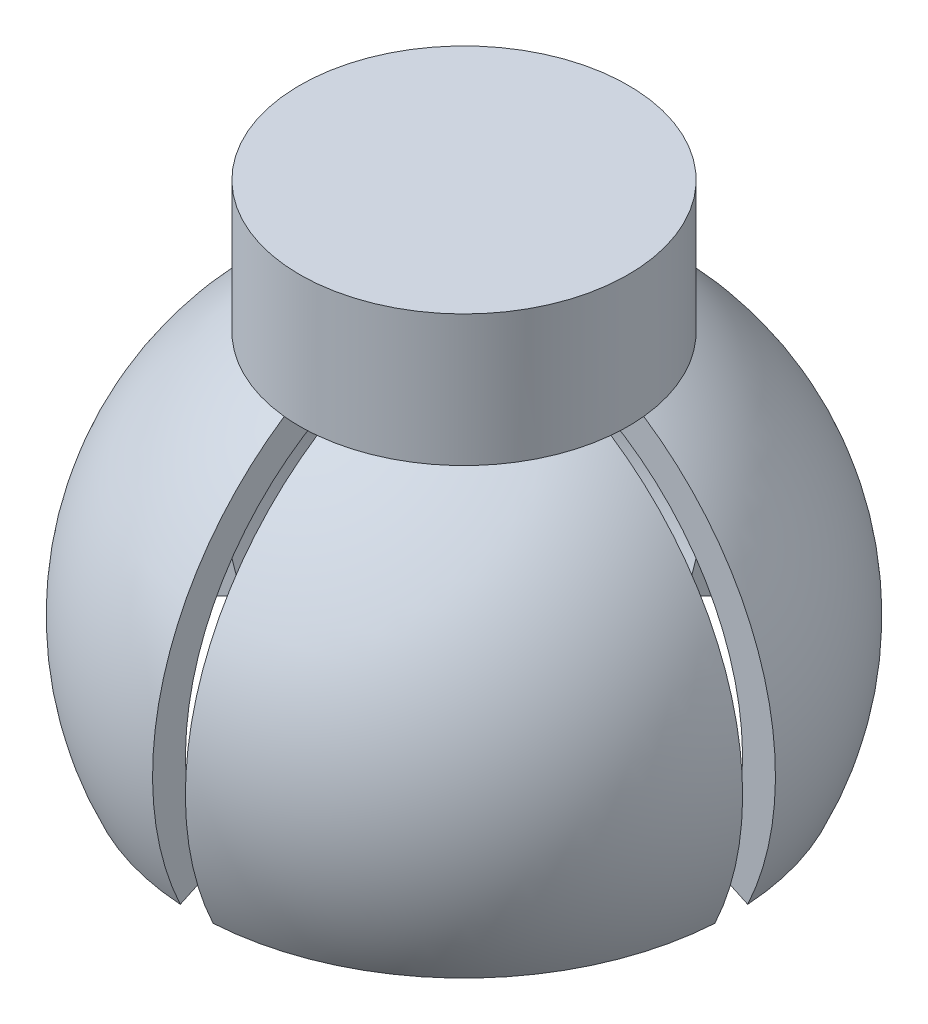
SolidWorks part; units mm, degrees
ref_plane "Front Plane" through (0, 0, 0) normal (0, 0, 1) x (1, 0, 0)
ref_plane "Top Plane" through (0, 0, 0) normal (0, 1, 0) x (1, 0, 0)
ref_plane "Right Plane" through (0, 0, 0) normal (1, 0, 0) x (0, 0, -1)
sketch "Sketch1" plane through (0, 0, 0) normal (0, 0, 1) x (1, 0, 0)
  line L1 (0, 5.7417) -> (0, 4)
  line L4 (3.6252, -1.6905) -> (4.0784, -1.9018)
  line L5 (0, 0) -> (3.8805, 0) construction
  line L6 (0, 0) -> (3.6252, -1.6905) construction
  line L9 (2.5, 5.7417) -> (0, 5.7417)
  line L10 (2.5, 3.7417) -> (2.5, 5.7417)
  arc A0 (3.6252, -1.6905) -> (0, 4) centre (0, 0) ccw
  arc A1 (4.0784, -1.9018) -> (2.5, 3.7417) centre (0, 0) ccw
  dimension "D1" = 4
  dimension "D2" = 9
  dimension "D3" = 25
  dimension "D4" = 2.5
  dimension "D5" = 2
revolve "Revolve1" add sketch "Sketch1" angle 360 about L1
sketch "Sketch2" plane through (0, 0, 0) normal (0, 0, 1) x (1, 0, 0)
  line L0 (-0.25, -1.9018) -> (-0.25, 3.7417)
  line L1 (-0.25, -1.9018) -> (0.25, -1.9018)
  line L2 (-0.25, 3.7417) -> (0.25, 3.7417)
  line L3 (0.25, -1.9018) -> (0.25, 3.7417)
  line L4 (4.0784, -1.9018) -> (-4.0784, -1.9018) construction
  line L5 (-2.5, 3.7417) -> (2.5, 3.7417) construction
  point P6 (0, 3.7417)
  dimension "D1" = 0.5
extrude "Cut-Extrude1" cut sketch "Sketch2" against normal blind 10
pattern_circular "CirPattern1" count 4 over 360 about axis through (0, 0, 0) along (0, 1, 0) of "Cut-Extrude1"
